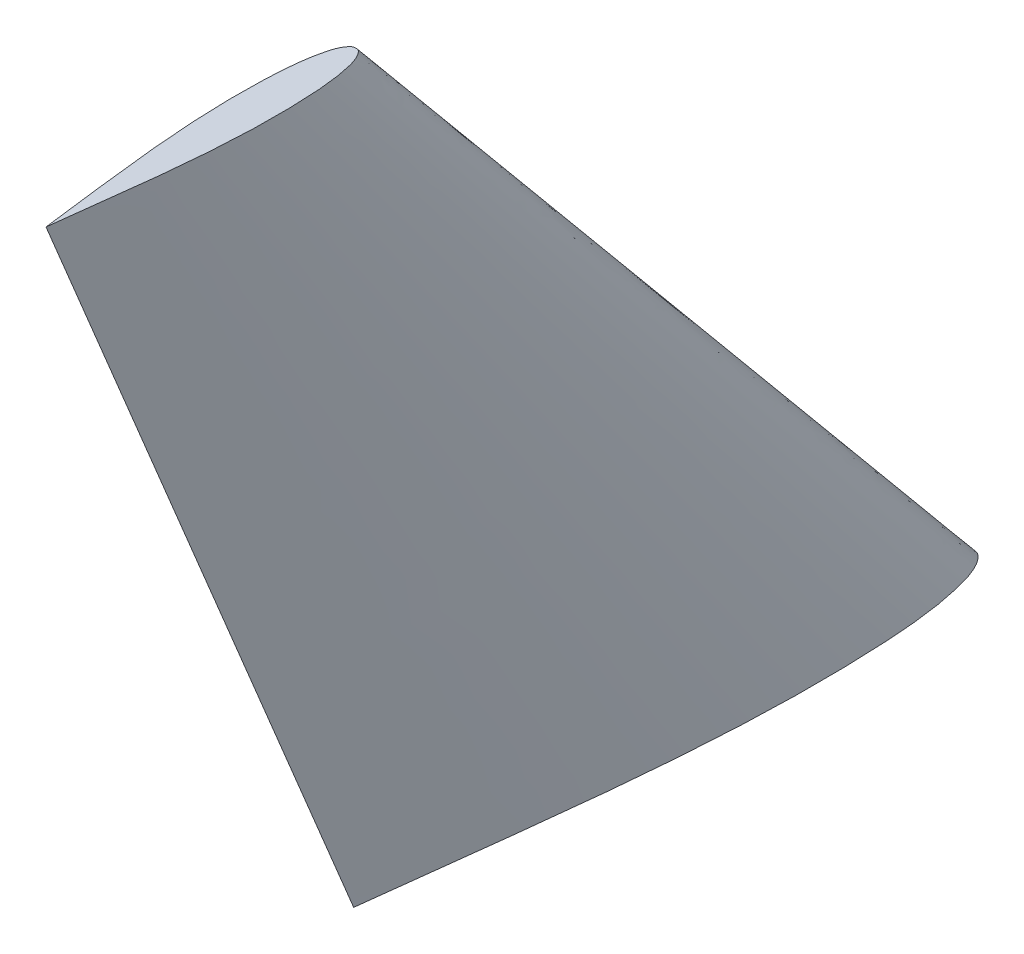
SolidWorks part; units mm, degrees
ref_plane "Front Plane" through (0, 0, 0) normal (0, 0, 1) x (1, 0, 0)
ref_plane "Top Plane" through (0, 0, 0) normal (0, 1, 0) x (1, 0, 0)
ref_plane "Right Plane" through (0, 0, 0) normal (1, 0, 0) x (0, 0, -1)
sketch "Sketch1" plane through (0, 0, 0) normal (0, 1, 0) x (1, 0, 0)
  line L0 (-215.8823, 1347.3324) -> (-486.544, 1347.3324) construction
  line L1 (0, -2790.1422) -> (0, 2790.1422) construction
  line L2 (-309.7777, -14582.8325) -> (-309.7777, -14310.2464) construction
  line L3 (423.7023, 3204.6344) -> (423.7023, 3740.6344) construction
  spline S0 degree 3 poles (0, 2790.1422) (32.4306, 2797.704) (84.2145, 2759.2657) (160.7843, 2647.8589) (216.2365, 2472.6267) (292.9453, 2117.6258) (431.0795, 352.4549) (168.4462, -1327.5077) (0, -2790.1422) knots 0 0 0 0 0.015892 0.031409 0.071418 0.111027 0.223281 1 1 1 1
  spline S1 degree 3 poles (0, 2790.1422) (-32.4306, 2797.704) (-84.2145, 2759.2657) (-160.7843, 2647.8589) (-216.2365, 2472.6267) (-292.9453, 2117.6258) (-431.0795, 352.4549) (-168.4462, -1327.5077) (0, -2790.1422) knots 0 0 0 0 0.015892 0.031409 0.071418 0.111027 0.223281 1 1 1 1
  point P6 (0, 0)
  dimension "D1" = 5580.2845
sketch "Sketch2" plane through (0, 0, 0) normal (1, 0, 0) x (0, 0, -1)
  line L0 (2790.1422, 0) -> (-2772.6535, 6696.456) construction
  line L1 (-2790.1422, 0) -> (2790.1422, 0) construction
  line L2 (-2790.1422, 0) -> (-5562.7952, 6696.456) construction
  line L3 (-5562.7952, 6696.456) -> (-2772.6535, 6696.456) construction
  line L4 (1395.0711, 0) -> (-3470.1889, 6696.456) construction
  line L5 (1553.9867, 1488.0757) -> (313.9209, 1488.0757) construction
  line L6 (313.9209, 1488.0757) -> (-3406.2767, 1488.0757) construction
  line L7 (313.9209, 1488.0757) -> (313.9209, 0) construction
  line L8 (1395.0711, 0) -> (1395.0711, 8848.7147) construction
  line L9 (-348.7678, 0) -> (-4342.1082, 6696.456) construction
  point P14 (0, 0)
  point P16 (-348.7678, 0)
  dimension "D1" = 1395.0711
  dimension "D2" = 5580.2845
  dimension "D3" = 2790.1416
  dimension "D4" = 697.5354
  dimension "D5" = 6696.456
  dimension "D6" = 1488.0757
  dimension "D7" = 36
  dimension "D8" = 3138.91
  dimension "D9" = 1569.4547
ref_plane "Plane1" through (0, 6696.456, 0) normal (0, 1, 0) x (1, 0, 0)
sketch "Sketch3" plane through (0, 6696.456, 0) normal (0, 1, 0) x (1, 0, 0)
  line L0 (0, -2772.6535) -> (0, -5562.7952) construction
  line L1 (1.5245, -5940.7532) -> (-755.8625, -5716.5827) construction
  spline S0 degree 3 poles (0, -2772.6535) (16.9799, -2767.1453) (40.1911, -2785.806) (82.3452, -2843.2421) (112.4634, -2942.3407) (146.9755, -3121.7235) (216.027, -4000.0579) (88.1787, -4833.0101) (0, -5562.7952) knots 0 0 0 0 0.016437 0.028569 0.075697 0.12246 0.221964 1 1 1 1
  spline S1 degree 3 poles (0, -2772.6535) (-16.9799, -2767.1453) (-40.1911, -2785.806) (-82.3452, -2843.2421) (-112.4634, -2942.3407) (-146.9755, -3121.7235) (-216.027, -4000.0579) (-88.1787, -4833.0101) (0, -5562.7952) knots 0 0 0 0 0.016437 0.028569 0.075697 0.12246 0.221964 1 1 1 1
loft "Loft2" add profiles "Sketch1", "Sketch3"
equation "\"D1@Sketch2\"=.25*\"D2@Sketch2\""
equation "\"D4@Sketch2\"=.25*\"D3@Sketch2\""
equation "\"D8@Sketch2\"=0.5625*\"D2@Sketch2\""
equation "\"D9@Sketch2\"=0.5625*\"D3@Sketch2\""
